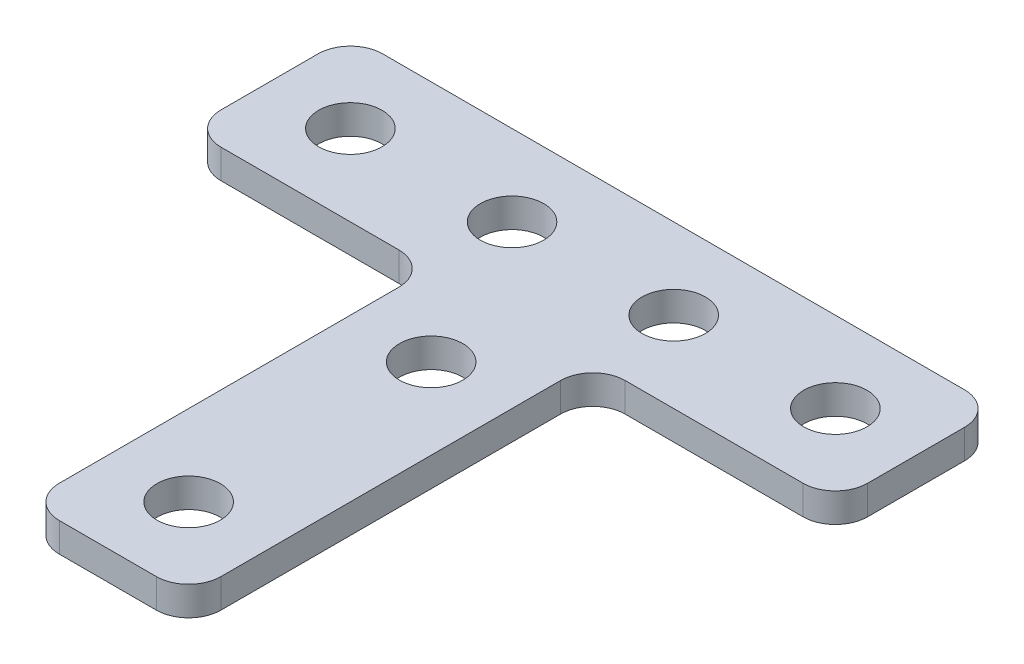
SolidWorks part; units mm, degrees
ref_plane "Front Plane" through (0, 0, 0) normal (0, 0, 1) x (1, 0, 0)
ref_plane "Top Plane" through (0, 0, 0) normal (0, 1, 0) x (1, 0, 0)
ref_plane "Right Plane" through (0, 0, 0) normal (1, 0, 0) x (0, 0, -1)
sketch "Sketch1" plane through (0, 0, 0) normal (0, 1, 0) x (1, 0, 0)
  line L1 (0, 0) -> (12.7, 0)
  line L2 (0, 0) -> (0, 31.75)
  line L3 (0, 31.75) -> (12.7, 31.75)
  line L4 (12.7, 0) -> (12.7, 31.75)
  line L5 (-19.0471, 31.75) -> (31.75, 31.75)
  line L6 (-19.0471, 31.75) -> (-19.0471, 44.45)
  line L7 (-19.0471, 44.45) -> (31.75, 44.45)
  line L8 (31.75, 31.75) -> (31.75, 44.45)
  circle A0 centre (6.35, 6.35) radius 2.4892
  circle A1 centre (6.35, 25.4) radius 2.4892
  circle A2 centre (0.0029, 38.1) radius 2.4892
  circle A3 centre (12.7029, 38.1) radius 2.4892
  circle A4 centre (25.4, 38.1) radius 2.4892
  circle A5 centre (-12.6971, 38.1) radius 2.4892
  dimension "D1" = 4.9784
  dimension "D2" = 6.35
  dimension "D4" = 19.05
  dimension "D5" = 6.35
  dimension "D8" = 12.7
  dimension "D9" = 12.7
  dimension "D10" = 6.35
  dimension "D11" = 6.35
  dimension "D13" = 19.05
  dimension "D15" = 6.35
  dimension "D16" = 19.0471
  dimension "D3" = 6.35
  dimension "D6" = 6.35
  dimension "D14" = 6.35
extrude "Boss-Extrude1" add sketch "Sketch1" along normal blind 2.286 contours L5 L8 L7 L6 L3 A5 A4 A3 A2 | L1 L4 L3 L2 A1 A0
fillet "Fillet1" radius 2.54 8 edges at (-19.0471, 1.143, -44.45) (-19.0471, 1.143, -31.75) (0, 1.143, -31.75) (31.75, 1.143, -44.45) (31.75, 1.143, -31.75) (12.7, 1.143, -31.75) (0, 1.143, 0) (12.7, 1.143, 0)
